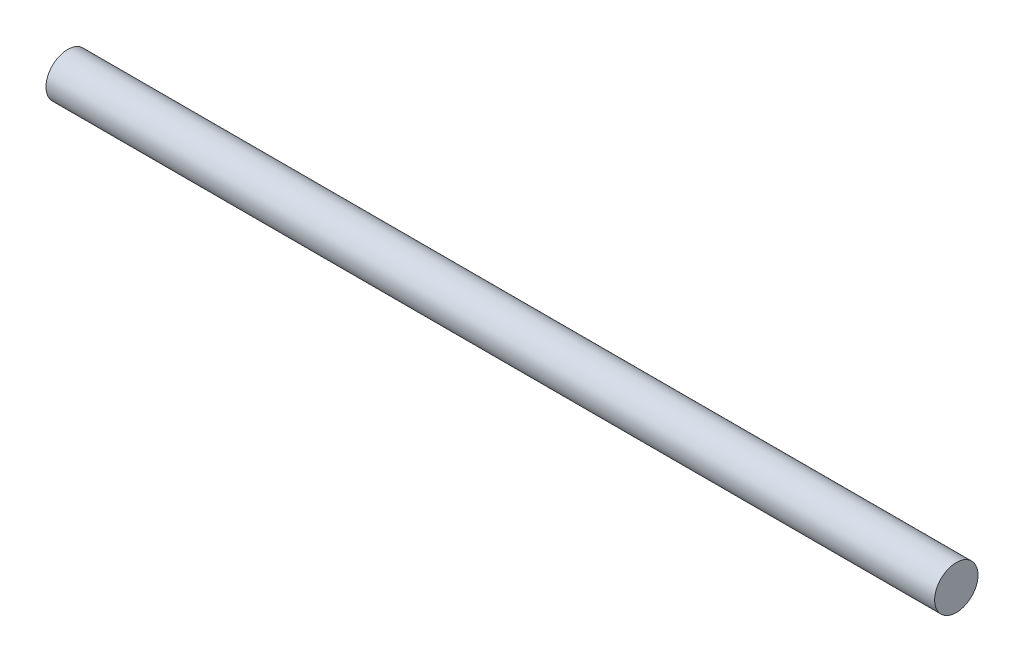
SolidWorks part; units mm, degrees
ref_plane "Front Plane" through (0, 0, 0) normal (0, 0, 1) x (1, 0, 0)
ref_plane "Top Plane" through (0, 0, 0) normal (0, 1, 0) x (1, 0, 0)
ref_plane "Right Plane" through (0, 0, 0) normal (1, 0, 0) x (0, 0, -1)
sketch "Sketch1" plane through (0, 0, 0) normal (1, 0, 0) x (0, 0, -1)
  circle A0 centre (0, 0) radius 21.082
  dimension "D1" = 42.164
extrude "Boss-Extrude1" add sketch "Sketch1" along normal blind 863.6
